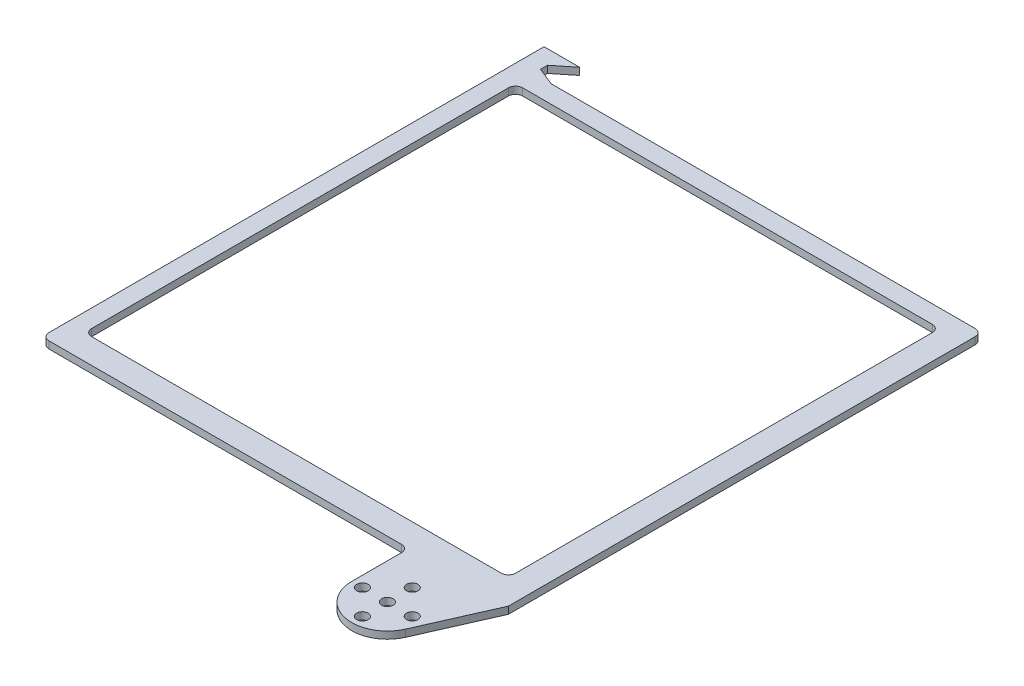
SolidWorks part; units mm, degrees
material "Thornel Mat VMA"
ref_plane "前视基准面" through (0, 0, 0) normal (0, 0, 1) x (1, 0, 0)
ref_plane "上视基准面" through (0, 0, 0) normal (0, 1, 0) x (1, 0, 0)
ref_plane "右视基准面" through (0, 0, 0) normal (1, 0, 0) x (0, 0, -1)
sketch "草图1" plane through (0, 0, 0) normal (0, 1, 0) x (1, 0, 0)
  line L0 (-28, -16) -> (-28, 0)
  line L1 (-28, 0) -> (-131, 0)
  line L2 (0, 0) -> (0, 133)
  line L3 (0, 133) -> (-131, 133)
  line L4 (-131, 0) -> (-131, 133)
  line L5 (0, 0) -> (-8.8527, -20.0407)
  arc A0 (-28, -16) -> (-8.8527, -20.0407) centre (-18, -16) ccw
  circle A1 centre (-18, -16) radius 7 construction
  circle A2 centre (-18, -9) radius 1.6
  circle A3 centre (-11, -16) radius 1.6
  circle A4 centre (-18, -23) radius 1.6
  circle A5 centre (-25, -16) radius 1.6
  circle A6 centre (-18, -16) radius 1.6
  dimension "D3" = 20
  dimension "D4" = 14
  dimension "D5" = 3.2
  dimension "D7" = 18
  dimension "D1" = 131
  dimension "D2" = 133
  dimension "D8" = 16
  dimension "D6" = 4
extrude "凸台-拉伸1" add sketch "草图1" along normal blind 2
sketch "草图2" plane through (0, 2, 0) normal (0, 1, 0) x (1, 0, 0)
  line L0 (-131, 133) -> (-131, 141)
  line L1 (-131, 141) -> (-121, 141)
  line L2 (-121, 141) -> (-126, 137)
  line L3 (-126, 137) -> (-126, 135)
  line L4 (-126, 135) -> (-121, 133)
  line L5 (0, 133) -> (-131, 133) construction
  line L6 (-121, 133) -> (-131, 133)
  dimension "D1" = 8
  dimension "D2" = 2
  dimension "D3" = 5
  dimension "D4" = 10
  dimension "D5" = 2
extrude "凸台-拉伸2" add sketch "草图2" against normal up to surface (2 mm away) up to face at (-46.9273, 0, -31.7422)
sketch "草图3" plane through (0, 2, 0) normal (0, 1, 0) x (1, 0, 0)
  line L0 (-131, 141) -> (-131, 0) construction
  line L1 (-124, 128) -> (-9, 128)
  line L2 (-126, 126) -> (-126, 9)
  line L3 (-124, 7) -> (-9, 7)
  line L4 (-7, 126) -> (-7, 9)
  line L5 (0, 133) -> (-121, 133) construction
  line L6 (0, 0) -> (0, 133) construction
  line L7 (-131, 0) -> (-28, 0) construction
  arc A0 (-126, 9) -> (-124, 7) centre (-124, 9) ccw
  arc A1 (-9, 7) -> (-7, 9) centre (-9, 9) ccw
  arc A2 (-9, 128) -> (-7, 126) centre (-9, 126) cw
  arc A3 (-124, 128) -> (-126, 126) centre (-124, 126) ccw
  dimension "D5" = 2
  dimension "D1" = 5
  dimension "D2" = 5
  dimension "D3" = 7
  dimension "D4" = 7
extrude "切除-拉伸1" cut sketch "草图3" against normal through all
fillet "圆角1" radius 2 3 edges at (-28, 1, 0) (-131, 1, 0) (0, 1, -133)
